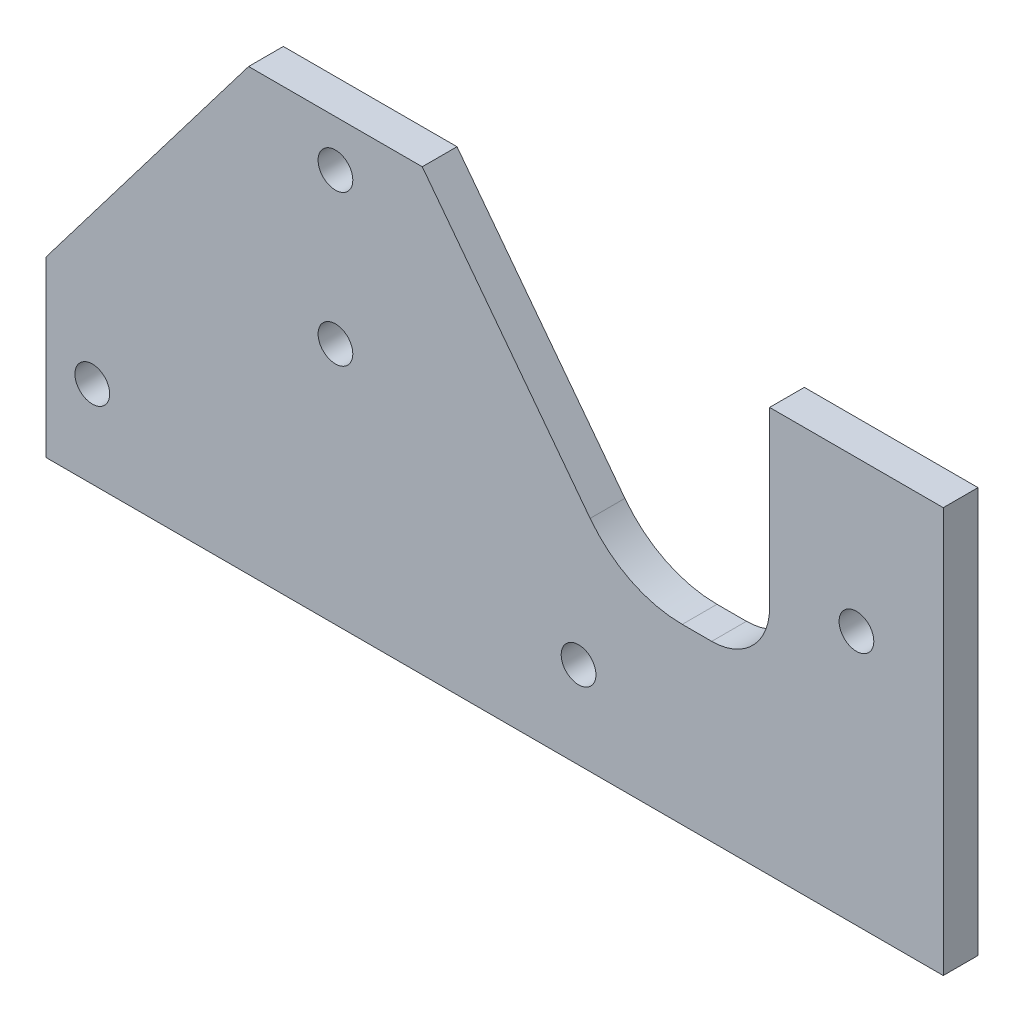
SolidWorks part; units mm, degrees
ref_plane "前视基准面" through (0, 0, 0) normal (0, 0, 1) x (1, 0, 0)
ref_plane "上视基准面" through (0, 0, 0) normal (0, 1, 0) x (1, 0, 0)
ref_plane "右视基准面" through (0, 0, 0) normal (1, 0, 0) x (0, 0, -1)
sketch "草图1" plane through (0, 0, 0) normal (0, 0, 1) x (1, 0, 0)
  line L0 (0, 0) -> (15, 0)
  line L1 (15, 0) -> (29.4985, -19.0552)
  line L2 (37.4568, -23) -> (40, -23)
  line L3 (45, -18) -> (45, -3)
  line L4 (45, -3) -> (60, -3)
  line L5 (60, -3) -> (60, -38)
  line L6 (60, -38) -> (-17.5, -38)
  line L7 (-17.5, -38) -> (-17.5, -23)
  line L8 (-17.5, -23) -> (0, 0)
  arc A0 (29.4985, -19.0552) -> (37.4568, -23) centre (37.4568, -13) ccw
  arc A1 (40, -23) -> (45, -18) centre (40, -18) ccw
  point P12 (32.5, -23)
  dimension "D10" = 10
  dimension "D11" = 5
  dimension "D1" = 15
  dimension "D2" = 15
  dimension "D3" = 15
  dimension "D4" = 45
  dimension "D5" = 35
  dimension "D6" = 38
  dimension "D7" = 15
  dimension "D8" = 17.5
  dimension "D9" = 17.5
extrude "凸台-拉伸1" add sketch "草图1" along normal blind 3
sketch "草图2" plane through (0, 0, 3) normal (0, 0, 1) x (1, 0, 0)
  line L0 (-17.5, -23) -> (-17.5, -38) construction
  line L1 (15, 0) -> (0, 0) construction
  line L2 (-17.5, -38) -> (60, -38) construction
  line L3 (60, -38) -> (60, -3) construction
  line L4 (60, -3) -> (45, -3) construction
  circle A0 centre (-13.5, -30.5) radius 1.5
  circle A1 centre (28.5, -30.5) radius 1.5
  circle A2 centre (7.5, -4) radius 1.5
  circle A3 centre (7.5, -17) radius 1.5
  circle A4 centre (52.5, -16) radius 1.5
  point P18 (0, 0)
  point P19 (7.5, 0)
  point P20 (0, 0)
  dimension "D6" = 3
  dimension "D1" = 4
  dimension "D2" = 42
  dimension "D3" = 4
  dimension "D4" = 13
  dimension "D5" = 7.5
  dimension "D7" = 7.5
  dimension "D8" = 13
extrude "切除-拉伸1" cut sketch "草图2" against normal blind 3
